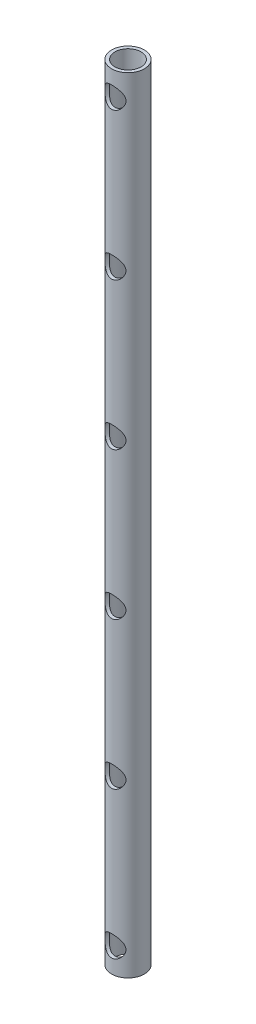
SolidWorks part; units mm, degrees
material "AISI 316  (SS)"
ref_plane "Front Plane" through (0, 0, 0) normal (0, 0, 1) x (1, 0, 0)
ref_plane "Top Plane" through (0, 0, 0) normal (0, 1, 0) x (1, 0, 0)
ref_plane "Right Plane" through (0, 0, 0) normal (1, 0, 0) x (0, 0, -1)
sketch "Sketch1" plane through (0, 0, 0) normal (0, 1, 0) x (1, 0, 0)
  circle A0 centre (0, 0) radius 16.7
  circle A1 centre (0, 0) radius 13.32
  dimension "D1" = 33.4
  dimension "D2" = 3.38
extrude "Boss-Extrude1" add sketch "Sketch1" along normal mid plane 800
sketch "Sketch2" plane through (0, 0, 0) normal (0, 0, 1) x (1, 0, 0)
  line L0 (13.32, 400) -> (-13.32, 400) construction
  circle A0 centre (0, 375) radius 10.75
  dimension "D1" = 21.5
  dimension "D2" = 25
extrude "Cut-Extrude1" cut sketch "Sketch2" along normal blind 40
pattern_linear "LPattern1" count 16 spacing 150 along (0, -1, 0) of "Cut-Extrude1"
